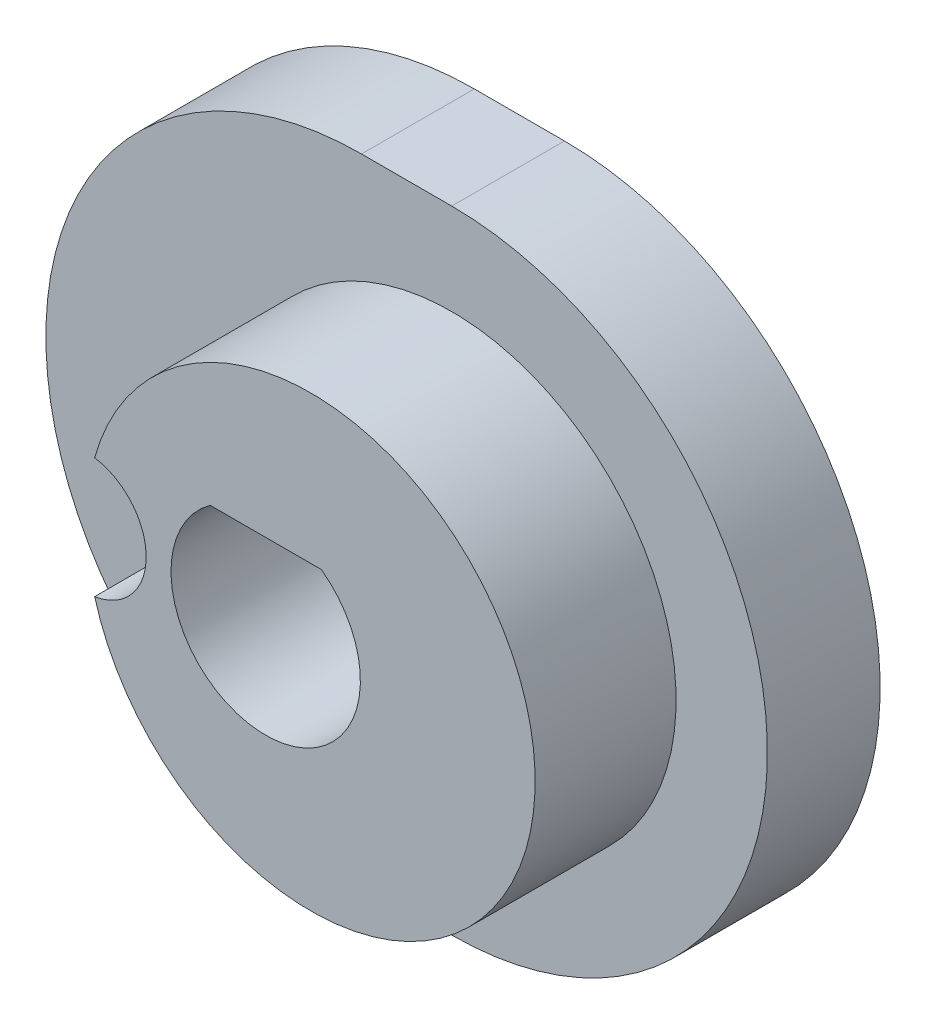
SolidWorks part; units mm, degrees
ref_plane "Front Plane" through (0, 0, 0) normal (0, 0, 1) x (1, 0, 0)
ref_plane "Top Plane" through (0, 0, 0) normal (0, 1, 0) x (1, 0, 0)
ref_plane "Right Plane" through (0, 0, 0) normal (1, 0, 0) x (0, 0, -1)
sketch "Sketch1" plane through (0, 0, 0) normal (0, 0, 1) x (1, 0, 0)
  line L0 (0, 0) -> (2.54, 0) construction
  line L1 (0, 8.89) -> (2.54, 8.89)
  line L2 (0, -8.89) -> (2.54, -8.89)
  arc A0 (0, 8.89) -> (0, -8.89) centre (0, 0) ccw
  arc A1 (2.54, -8.89) -> (2.54, 8.89) centre (2.54, 0) ccw
  dimension "D1" = 17.78
  dimension "D3" = 17.78
  dimension "D2" = 2.54
extrude "Boss-Extrude1" add sketch "Sketch1" along normal blind 3.175
sketch "Sketch4" plane through (0, 0, 3.175) normal (0, 0, 1) x (1, 0, 0)
  circle A1 centre (2.54, 0) radius 6.3183
  arc A2 (2.54, -8.89) -> (2.54, 8.89) centre (2.54, 0) ccw construction
  dimension "D1" = 12.6365
extrude "Boss-Extrude2" add sketch "Sketch4" along normal blind 3.9688
sketch "Sketch2" plane through (0, 0, 3.175) normal (0, 0, 1) x (1, 0, 0)
  line L0 (0, 0) -> (-3.81, 0) construction
  line L1 (0, 0) -> (1.27, 0) construction
  line L3 (2.8358, 2.159) -> (-0.2958, 2.159) construction
  line L4 (2.8358, 2.159) -> (-0.2958, 2.159)
  circle A0 centre (-3.81, 0) radius 0.9
  arc A2 (-0.2958, 2.159) -> (2.8358, 2.159) centre (1.27, 0) ccw construction
  arc A3 (-0.2958, 2.159) -> (2.8358, 2.159) centre (1.27, 0) ccw
  dimension "D3" = 1.8
  dimension "D1" = 1.27
  dimension "D2" = 3.81
extrude "Cut-Extrude1" cut sketch "Sketch2" against normal through all and the other way through all
sketch "Sketch3" plane through (0, 0, 3.175) normal (0, 0, 1) x (1, 0, 0)
  line L0 (0, 0) -> (-3.81, 0) construction
  circle A0 centre (-3.81, 0) radius 1.7145
  dimension "D2" = 3.429
  dimension "D1" = 3.81
extrude "Cut-Extrude2" cut sketch "Sketch3" against normal blind 3.81 and the other way through all
sketch "Sketch5" plane through (0, 0, 7.1437) normal (0, 0, 1) x (1, 0, 0)
  line L0 (0, 0) -> (6.35, 0) construction
  circle A0 centre (6.35, 0) radius 0.9
  dimension "D2" = 1.8
  dimension "D1" = 6.35
extrude "Cut-Extrude3" [suppressed] cut sketch "Sketch5" against normal blind 2.54
